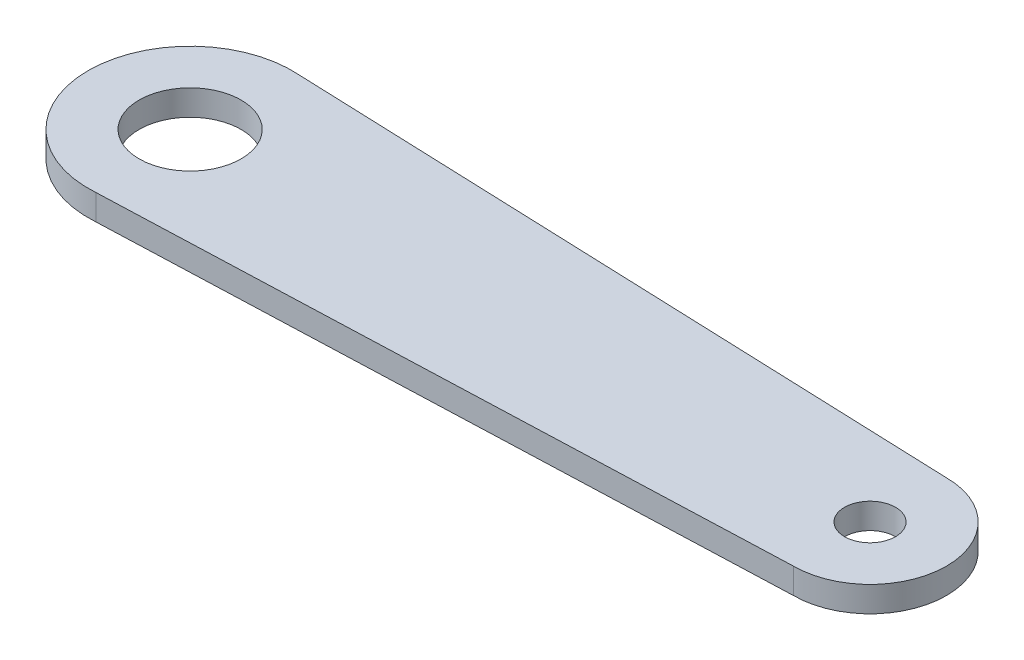
SolidWorks part; units mm, degrees
ref_plane "Front Plane" through (0, 0, 0) normal (0, 0, 1) x (1, 0, 0)
ref_plane "Top Plane" through (0, 0, 0) normal (0, 1, 0) x (1, 0, 0)
ref_plane "Right Plane" through (0, 0, 0) normal (1, 0, 0) x (0, 0, -1)
sketch "Sketch1" plane through (0, 0, 0) normal (0, 1, 0) x (1, 0, 0)
  line L0 (0.4494, 5.9831) -> (40, 4.5)
  line L1 (0.4494, -5.9831) -> (40, -4.5)
  arc A0 (0.4494, 5.9831) -> (0.4494, -5.9831) centre (0, 0) ccw
  arc A1 (40, -4.5) -> (40, 4.5) centre (40, 0) ccw
  dimension "D2" = 6
  dimension "D3" = 4.5
  dimension "D1" = 40
extrude "Boss-Extrude1" add sketch "Sketch1" along normal blind 1.5 contours L1 A1 L0 A0
sketch "Sketch2" plane through (0, 1.5, 0) normal (0, 1, 0) x (1, 0, 0)
  circle A0 centre (0, 0) radius 3
  circle A1 centre (40, 0) radius 1.5
  dimension "D1" = 6
  dimension "D2" = 3
extrude "Cut-Extrude1" cut sketch "Sketch2" against normal blind 10.5 and the other way blind 16
